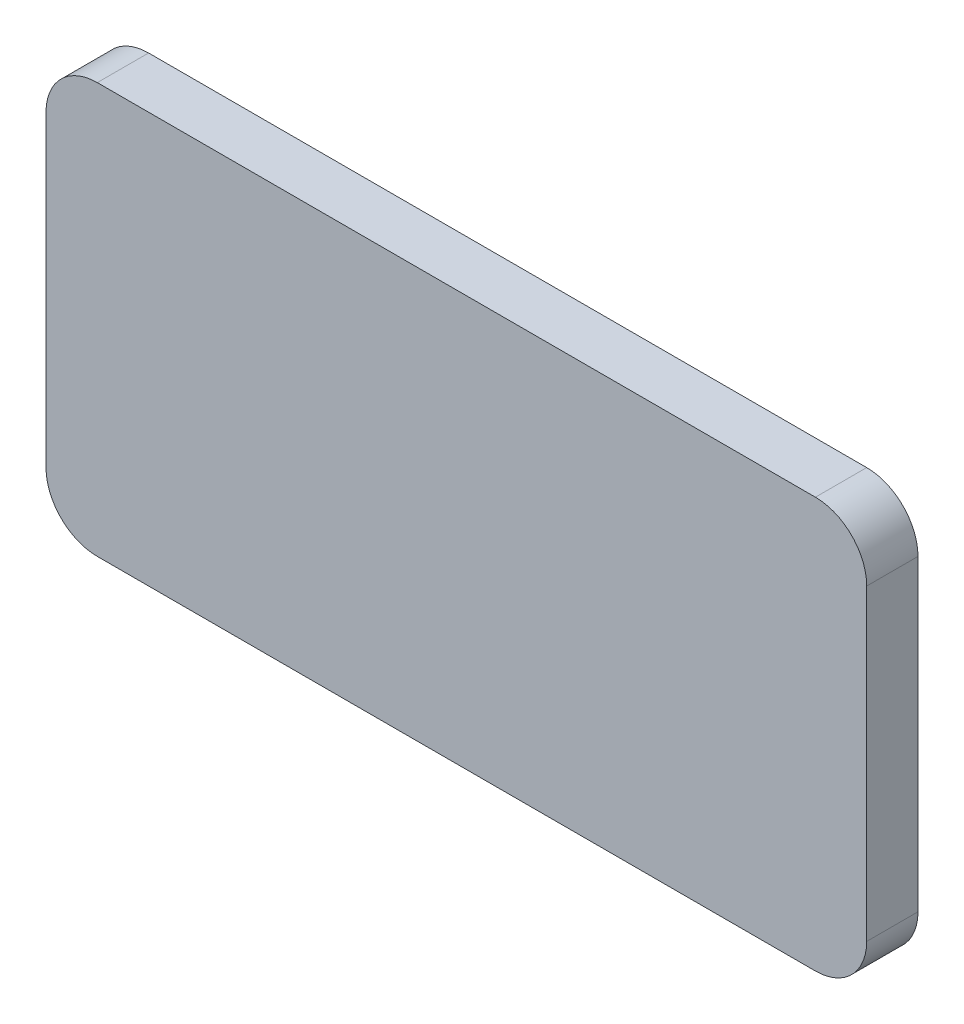
SolidWorks part; units mm, degrees
ref_plane "Front Plane" through (0, 0, 0) normal (0, 0, 1) x (1, 0, 0)
ref_plane "Top Plane" through (0, 0, 0) normal (0, 1, 0) x (1, 0, 0)
ref_plane "Right Plane" through (0, 0, 0) normal (1, 0, 0) x (0, 0, -1)
sketch "草圖1" plane through (0, 0, 0) normal (0, 0, 1) x (1, 0, 0)
  line L1 (5, 0) -> (75, 0)
  line L2 (0, 5) -> (0, 35)
  line L3 (5, 40) -> (75, 40)
  line L4 (80, 5) -> (80, 35)
  arc A0 (80, 35) -> (75, 40) centre (75, 35) ccw
  arc A1 (75, 0) -> (80, 5) centre (75, 5) ccw
  arc A2 (5, 0) -> (0, 5) centre (5, 5) cw
  arc A3 (0, 35) -> (5, 40) centre (5, 35) cw
  point P9 (80, 40)
  point P14 (0, 0)
  point P17 (0, 40)
  dimension "D4" = 5
  dimension "D1" = 40
  dimension "D2" = 80
  dimension "D3" = 0
extrude "填料-伸長1" add sketch "草圖1" along normal blind 5
